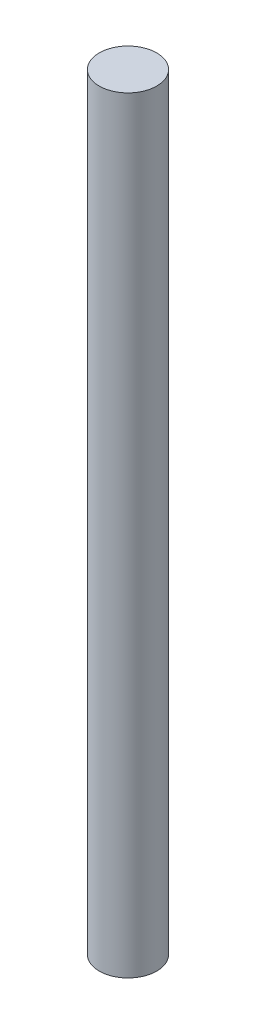
SolidWorks part; units mm, degrees
ref_plane "Front Plane" through (0, 0, 0) normal (0, 0, 1) x (1, 0, 0)
ref_plane "Top Plane" through (0, 0, 0) normal (0, 1, 0) x (1, 0, 0)
ref_plane "Right Plane" through (0, 0, 0) normal (1, 0, 0) x (0, 0, -1)
sketch "Sketch1" plane through (0, 0, 0) normal (0, 1, 0) x (1, 0, 0)
  circle A0 centre (0, 1.4399) radius 1.5
  dimension "D1" = 3
extrude "Boss-Extrude1" add sketch "Sketch1" along normal blind 40
